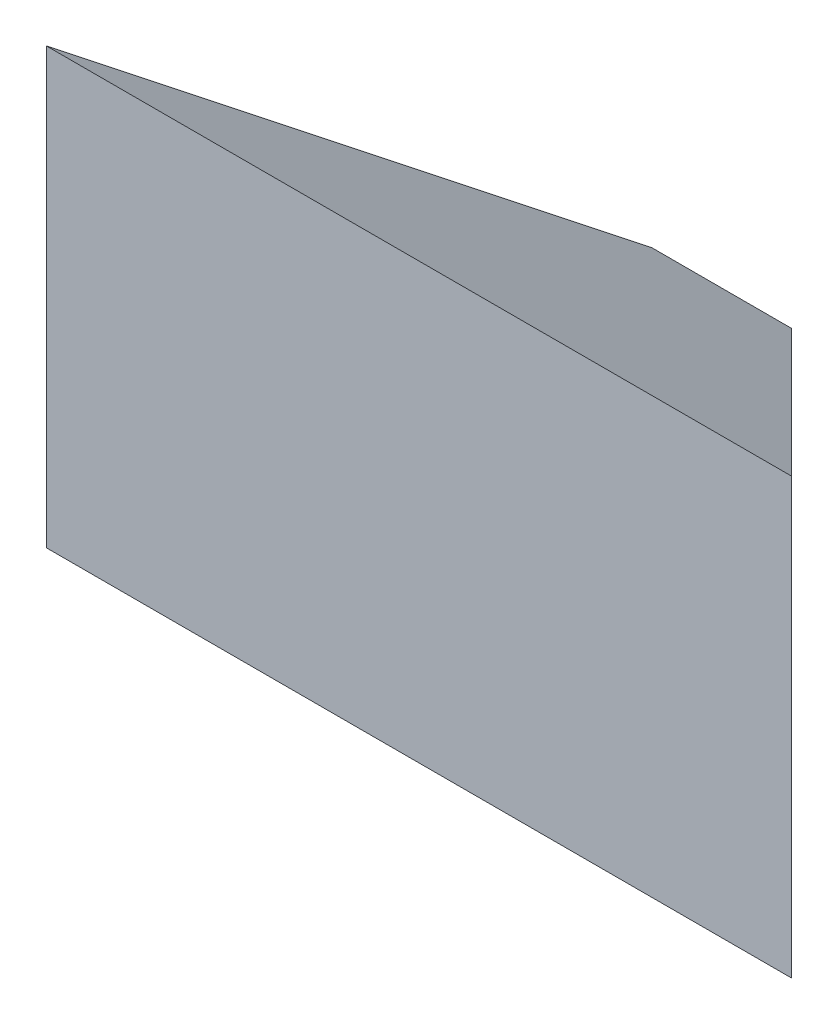
SolidWorks part; units mm, degrees
ref_plane "Front Plane" through (0, 0, 0) normal (0, 0, 1) x (1, 0, 0)
ref_plane "Top Plane" through (0, 0, 0) normal (0, 1, 0) x (1, 0, 0)
ref_plane "Right Plane" through (0, 0, 0) normal (1, 0, 0) x (0, 0, -1)
sketch "Sketch1" plane through (0, 0, 0) normal (0, 0, 1) x (1, 0, 0)
  line L0 (-11.5032, 17.0352) -> (11.5032, 17.0352) construction
  line L1 (-11.5, 1) -> (11.5, 1)
  line L2 (-11.5, 1) -> (-11.5, 15.0352)
  line L3 (-11.5, 15.0352) -> (11.5, 15.0352)
  line L4 (11.5, 1) -> (11.5, 15.0352)
  line L5 (-11.5, 1) -> (11.5, 15.0352) construction
  line L6 (-11.5, 15.0352) -> (11.5, 1) construction
  line L7 (-12.0858, -1) -> (12.0858, -1) construction
  line L8 (0, 8.0176) -> (0, 0) construction
  point P0 (0, 8.0176)
  dimension "D1" = 2
  dimension "D2" = 2
  dimension "D3" = 23
ref_plane "Plane1" through (0, 0, 50) normal (0, 0, 1) x (1, 0, 0)
sketch "Sketch2" plane through (0, 0, 50) normal (0, 0, 1) x (1, 0, 0)
  line L0 (-11.5, 15.0352) -> (11.5, 15.0352) construction
  line L1 (-61.5, -27.8684) -> (61.5, -27.8684)
  line L2 (-61.5, -27.8684) -> (-61.5, 43.9036)
  line L3 (-61.5, 43.9036) -> (61.5, 43.9036)
  line L4 (61.5, -27.8684) -> (61.5, 43.9036)
  line L5 (-61.5, -27.8684) -> (61.5, 43.9036) construction
  line L6 (-61.5, 43.9036) -> (61.5, -27.8684) construction
  line L7 (11.5, 1) -> (11.5, 15.0352) construction
  point P0 (0, 8.0176)
  dimension "D1" = 28.8684
  dimension "D2" = 50
loft "Loft1" add profiles "Sketch1", "Sketch2"
